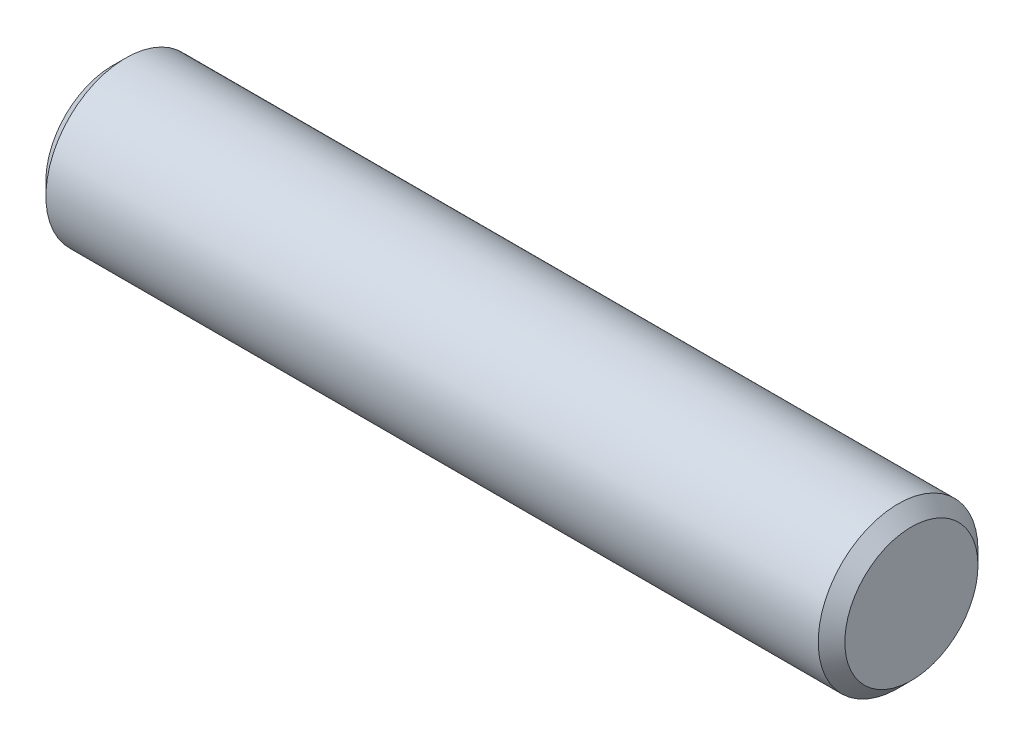
SolidWorks part; units mm, degrees
material "Простая углеродистая сталь"
ref_plane "Спереди" through (0, 0, 0) normal (0, 0, 1) x (1, 0, 0)
ref_plane "Сверху" through (0, 0, 0) normal (0, 1, 0) x (1, 0, 0)
ref_plane "Справа" through (0, 0, 0) normal (1, 0, 0) x (0, 0, -1)
sketch "Эскиз1" plane through (0, 0, 0) normal (1, 0, 0) x (0, 0, -1)
  circle A0 centre (0, 0) radius 3
  dimension "D1" = 6
extrude "Бобышка-Вытянуть1" add sketch "Эскиз1" along normal mid plane 30
chamfer "Фаска1" distance 0.5 angle 45 2 edges at (-15, 0, -3) (15, 0, -3)
